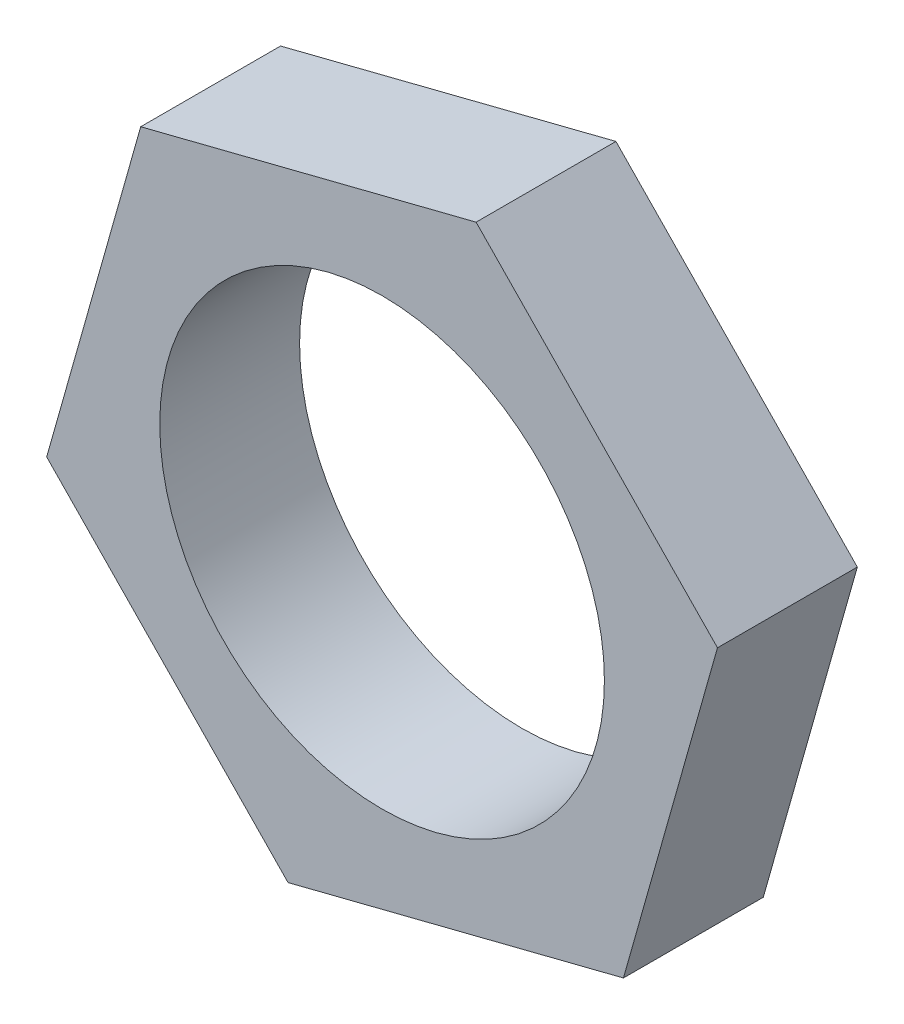
SolidWorks part; units mm, degrees
material "AISI 316 Annealed Stainless Steel Bar (SS)"
ref_plane "Front Plane" through (0, 0, 0) normal (0, 0, 1) x (1, 0, 0)
ref_plane "Top Plane" through (0, 0, 0) normal (0, 1, 0) x (1, 0, 0)
ref_plane "Right Plane" through (0, 0, 0) normal (1, 0, 0) x (0, 0, -1)
sketch "Sketch1" plane through (0, 0, 0) normal (0, 0, 1) x (1, 0, 0)
  line L1 (-1.3449, -4.7629) -> (3.4523, -3.5462)
  line L2 (3.4523, -3.5462) -> (4.7972, 1.2167)
  line L3 (4.7972, 1.2167) -> (1.3449, 4.7629)
  line L4 (1.3449, 4.7629) -> (-3.4523, 3.5462)
  line L5 (-3.4523, 3.5462) -> (-4.7972, -1.2167)
  line L6 (-4.7972, -1.2167) -> (-1.3449, -4.7629)
  circle A0 centre (0, 0) radius 4.286 construction
  circle A1 centre (0, 0) radius 3.18
  dimension "D1" = 6.36
extrude "Boss-Extrude1" add sketch "Sketch1" along normal blind 2
cosmetic thread "Cosmetic Thread1"
